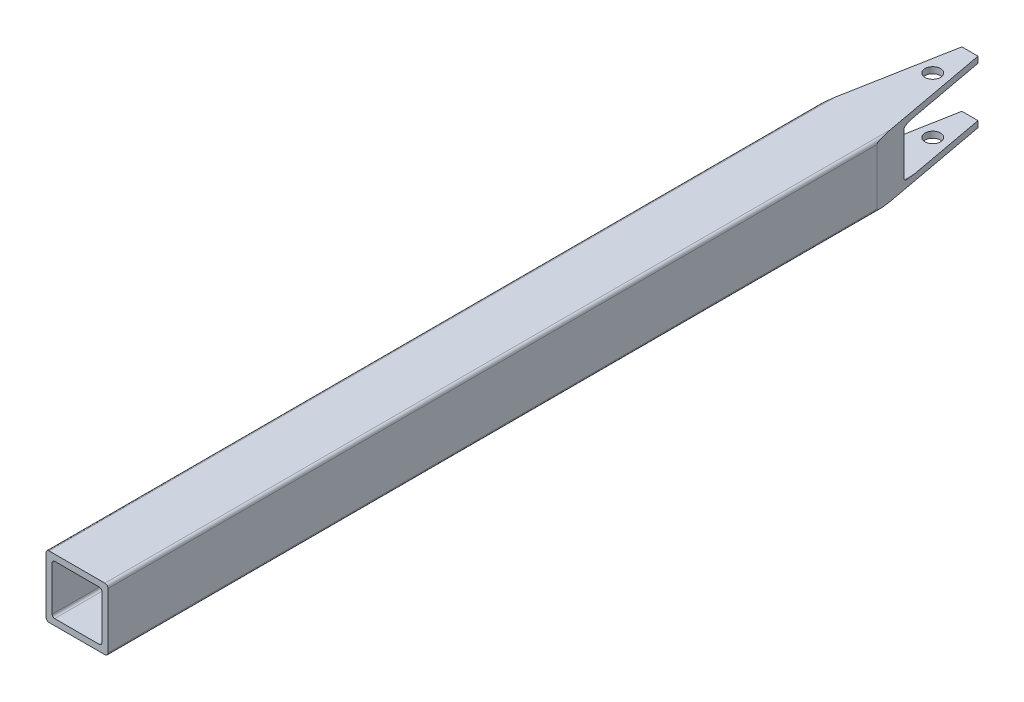
SolidWorks part; units mm, degrees
ref_plane "Front" through (0, 0, 0) normal (0, 0, 1) x (1, 0, 0)
ref_plane "Top" through (0, 0, 0) normal (0, 1, 0) x (1, 0, 0)
ref_plane "Right" through (0, 0, 0) normal (1, 0, 0) x (0, 0, -1)
sketch "Sketch1" plane through (0, 0, 0) normal (0, 0, 1) x (1, 0, 0)
  line L0 (-25.4, 0) -> (-31.75, 0) construction
  line L1 (28.575, -31.75) -> (-28.575, -31.75)
  line L2 (31.75, -28.575) -> (31.75, 28.575)
  line L3 (28.575, 31.75) -> (-28.575, 31.75)
  line L4 (-31.75, -28.575) -> (-31.75, 28.575)
  line L5 (31.75, -31.75) -> (-31.75, 31.75) construction
  line L6 (31.75, 31.75) -> (-31.75, -31.75) construction
  line L7 (22.86, 25.4) -> (-22.86, 25.4)
  line L8 (25.4, 22.86) -> (25.4, -22.86)
  line L9 (22.86, -25.4) -> (-22.86, -25.4)
  line L10 (-25.4, 22.86) -> (-25.4, -22.86)
  line L11 (25.4, 25.4) -> (-25.4, -25.4) construction
  line L12 (25.4, -25.4) -> (-25.4, 25.4) construction
  line L13 (0, -25.4) -> (0, -31.75) construction
  line L14 (25.4, -22.86) -> (25.4, -31.75) construction
  line L16 (25.4, -31.75) -> (31.75, -31.75) construction
  arc A0 (-22.86, -25.4) -> (-25.4, -22.86) centre (-22.86, -22.86) cw
  arc A1 (25.4, -22.86) -> (22.86, -25.4) centre (22.86, -22.86) cw
  arc A2 (22.86, 25.4) -> (25.4, 22.86) centre (22.86, 22.86) cw
  arc A3 (-22.86, 25.4) -> (-25.4, 22.86) centre (-22.86, 22.86) ccw
  arc A4 (28.575, -31.75) -> (31.75, -28.575) centre (28.575, -28.575) ccw
  arc A5 (31.75, 28.575) -> (28.575, 31.75) centre (28.575, 28.575) ccw
  arc A6 (-28.575, 31.75) -> (-31.75, 28.575) centre (-28.575, 28.575) ccw
  arc A7 (-28.575, -31.75) -> (-31.75, -28.575) centre (-28.575, -28.575) cw
  point P0 (0, 0)
  point P6 (0, 0)
  dimension "D2" = 2.54
  dimension "D3" = 3.175
sketch "Sketch2" plane through (0, 0, 0) normal (1, 0, 0) x (0, 0, -1)
  line L0 (-457.2, 0) -> (457.2, 0) construction
  dimension "Length" = 914.4
ref_plane "Plane1" through (31.75, 0, 0) normal (1, 0, 0) x (0, 0, -1)
sketch "Sketch5" plane through (31.75, 0, 0) normal (1, 0, 0) x (0, 0, -1)
  line L0 (-457.2, 31.75) -> (-457.2, -31.75) construction
  line L1 (457.2, 31.75) -> (457.2, -31.75) construction
sketch "Sketch4" plane through (0, 0, 0) normal (0, 0, 1) x (1, 0, 0)
  line L0 (31.75, -28.575) -> (31.75, 28.575) construction
  line L1 (28.575, 31.75) -> (-28.575, 31.75) construction
  line L2 (-31.75, -28.575) -> (-31.75, 28.575) construction
  line L3 (28.575, -31.75) -> (-28.575, -31.75) construction
  line L4 (25.4, 22.86) -> (25.4, -22.86) construction
  line L5 (22.86, -25.4) -> (-22.86, -25.4) construction
  line L6 (-25.4, 22.86) -> (-25.4, -22.86) construction
  line L7 (22.86, 25.4) -> (-22.86, 25.4) construction
  line L8 (31.75, -28.575) -> (31.75, 28.575)
  line L9 (28.575, 31.75) -> (-28.575, 31.75)
  line L10 (-31.75, -28.575) -> (-31.75, 28.575)
  line L11 (28.575, -31.75) -> (-28.575, -31.75)
  line L12 (25.4, 22.86) -> (25.4, -22.86)
  line L13 (22.86, -25.4) -> (-22.86, -25.4)
  line L14 (-25.4, 22.86) -> (-25.4, -22.86)
  line L15 (22.86, 25.4) -> (-22.86, 25.4)
  arc A0 (31.75, 28.575) -> (28.575, 31.75) centre (28.575, 28.575) ccw construction
  arc A1 (-28.575, 31.75) -> (-31.75, 28.575) centre (-28.575, 28.575) ccw construction
  arc A2 (-31.75, -28.575) -> (-28.575, -31.75) centre (-28.575, -28.575) ccw construction
  arc A3 (28.575, -31.75) -> (31.75, -28.575) centre (28.575, -28.575) ccw construction
  arc A4 (22.86, -25.4) -> (25.4, -22.86) centre (22.86, -22.86) ccw construction
  arc A5 (-25.4, -22.86) -> (-22.86, -25.4) centre (-22.86, -22.86) ccw construction
  arc A6 (-22.86, 25.4) -> (-25.4, 22.86) centre (-22.86, 22.86) ccw construction
  arc A7 (25.4, 22.86) -> (22.86, 25.4) centre (22.86, 22.86) ccw construction
  arc A8 (31.75, 28.575) -> (28.575, 31.75) centre (28.575, 28.575) ccw
  arc A9 (-28.575, 31.75) -> (-31.75, 28.575) centre (-28.575, 28.575) ccw
  arc A10 (-31.75, -28.575) -> (-28.575, -31.75) centre (-28.575, -28.575) ccw
  arc A11 (28.575, -31.75) -> (31.75, -28.575) centre (28.575, -28.575) ccw
  arc A12 (22.86, -25.4) -> (25.4, -22.86) centre (22.86, -22.86) ccw
  arc A13 (-25.4, -22.86) -> (-22.86, -25.4) centre (-22.86, -22.86) ccw
  arc A14 (-22.86, 25.4) -> (-25.4, 22.86) centre (-22.86, 22.86) ccw
  arc A15 (25.4, 22.86) -> (22.86, 25.4) centre (22.86, 22.86) ccw
extrude "Boss-Extrude1" add sketch "Sketch4" along normal up to vertex (457.2 mm away) and the other way up to vertex (457.2 mm away) up to point (0, 0, 457.2) other way up to point (0, 0, -457.2)
sketch "Sketch6" plane through (0, 31.75, 0) normal (0, 1, 0) x (1, 0, 0)
  line L0 (-31.75, 457.2) -> (31.75, 457.2) construction
  line L1 (-8.255, 457.2) -> (8.255, 457.2) construction
  line L2 (8.255, 457.2) -> (31.75, 330.2)
  line L3 (31.75, -457.2) -> (31.75, 457.2) construction
  line L4 (31.75, 330.2) -> (31.75, 457.2)
  line L5 (31.75, 457.2) -> (8.255, 457.2)
  line L6 (-8.255, 457.2) -> (-31.75, 330.2)
  line L7 (-31.75, -457.2) -> (-31.75, 457.2) construction
  line L8 (-31.75, 330.2) -> (-31.75, 457.2)
  line L9 (-31.75, 457.2) -> (-8.255, 457.2)
  line L10 (0, 457.2) -> (0, 419.1) construction
  circle A0 centre (0, 419.1) radius 7.9375
  point P7 (0, 457.2)
  point P17 (0, 0)
  dimension "D1" = 15.875
  dimension "D2" = 16.51
  dimension "D3" = 127
  dimension "D4" = 38.1
extrude "Cut-Extrude1" cut sketch "Sketch6" against normal through all
equation "\"D3@Sketch1\"=\"Outside Width@Sketch1\"*.05"
equation "\"D2@Sketch1\"=\"D1@Sketch1\"*.05"
